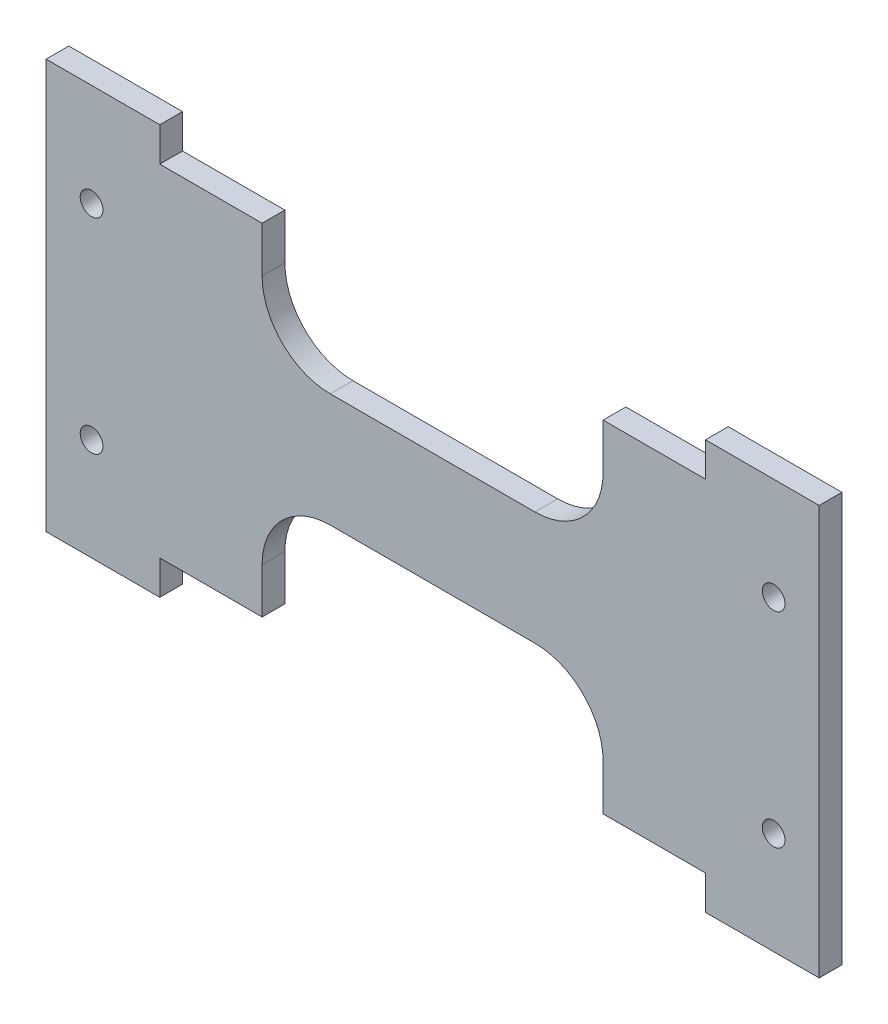
SolidWorks part; units mm, degrees
ref_plane "Спереди" through (0, 0, 0) normal (0, 0, 1) x (1, 0, 0)
ref_plane "Сверху" through (0, 0, 0) normal (0, 1, 0) x (1, 0, 0)
ref_plane "Справа" through (0, 0, 0) normal (1, 0, 0) x (0, 0, -1)
sketch "Model" plane through (0, 0, 0) normal (0, 0, 1) x (1, 0, 0)
  line L0 (15, 20) -> (24, 20)
  line L1 (24, 20) -> (24, 23)
  line L2 (24, 23) -> (34, 23)
  line L3 (34, 23) -> (34, -13)
  line L4 (34, -13) -> (24, -13)
  line L5 (24, -13) -> (24, -10)
  line L6 (24, -10) -> (15, -10)
  line L7 (15, -10) -> (15, -6)
  line L8 (9, 0) -> (-9, 0)
  line L9 (-15, -6) -> (-15, -10)
  line L10 (-15, -10) -> (-24, -10)
  line L11 (-24, -10) -> (-24, -13)
  line L12 (-24, -13) -> (-34, -13)
  line L13 (-34, -13) -> (-34, 23)
  line L14 (-34, 23) -> (-24, 23)
  line L15 (-24, 23) -> (-24, 20)
  line L16 (-24, 20) -> (-15, 20)
  line L17 (-15, 20) -> (-15, 16)
  line L18 (-9, 10) -> (9, 10)
  line L19 (15, 16) -> (15, 20)
  circle A0 centre (30, -4) radius 1
  circle A1 centre (30, 14) radius 1
  circle A2 centre (-30, 14) radius 1
  circle A3 centre (-30, -4) radius 1
  arc A4 (15, -6) -> (9, 0) centre (9, -6) ccw
  arc A5 (-9, 0) -> (-15, -6) centre (-9, -6) ccw
  arc A6 (-15, 16) -> (-9, 10) centre (-9, 16) ccw
  arc A7 (9, 10) -> (15, 16) centre (9, 16) ccw
extrude "Бобышка-Вытянуть1" add sketch "Model" along normal blind 2
